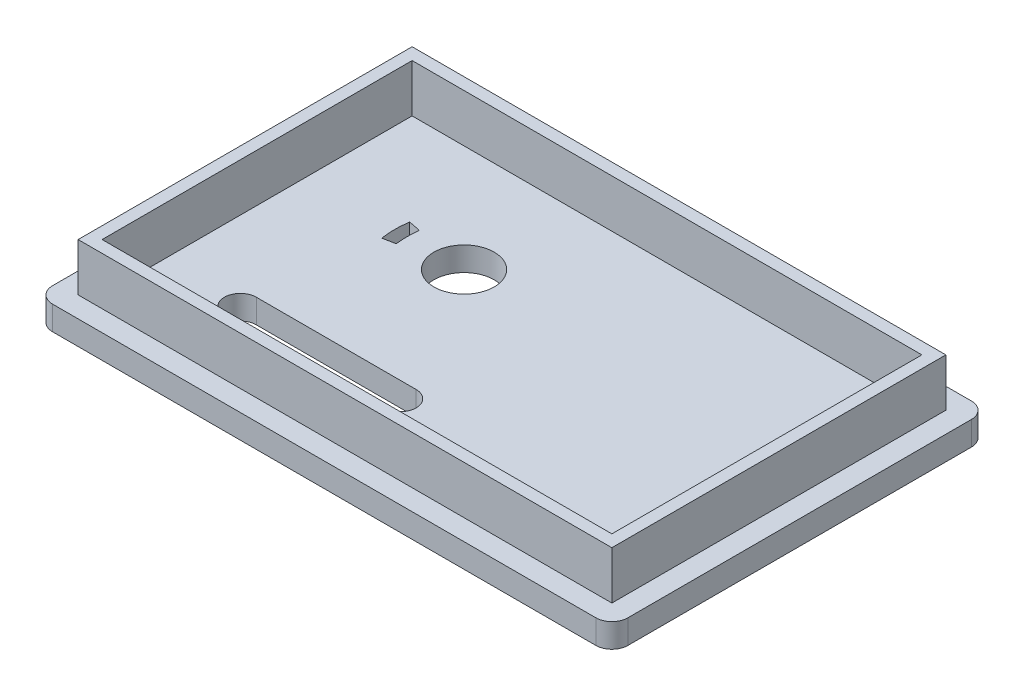
SolidWorks part; units mm, degrees
ref_plane "Front Plane" through (0, 0, 0) normal (0, 0, 1) x (1, 0, 0)
ref_plane "Top Plane" through (0, 0, 0) normal (0, 1, 0) x (1, 0, 0)
ref_plane "Right Plane" through (0, 0, 0) normal (1, 0, 0) x (0, 0, -1)
sketch "Sketch2" plane through (0, 0, 0) normal (0, 1, 0) x (1, 0, 0)
  line L1 (0, 0) -> (72, 0)
  line L2 (0, 0) -> (0, 47)
  line L3 (0, 47) -> (72, 47)
  line L4 (72, 0) -> (72, 47)
  dimension "D1" = 72
  dimension "D2" = 47
extrude "Boss-Extrude1" add sketch "Sketch2" along normal blind 3 contours L3 L4 L1 L2
fillet "Fillet1" radius 2 4 edges at (0, 1.5, 0) (0, 1.5, -47) (72, 1.5, -47) (72, 1.5, 0)
sketch "Sketch3" plane through (0, 3, 0) normal (0, 1, 0) x (1, 0, 0)
  line L0 (0, 2) -> (0, 45) construction
  line L1 (2.5, 44.5) -> (69.5, 44.5) construction
  line L2 (2.5, 44.5) -> (2.5, 2.5) construction
  line L3 (2.5, 2.5) -> (69.5, 2.5) construction
  line L4 (69.5, 44.5) -> (69.5, 2.5) construction
  line L5 (2, 0) -> (70, 0) construction
  line L6 (2.6, 44.4) -> (69.4, 44.4)
  line L7 (69.4, 44.4) -> (69.4, 2.6)
  line L8 (2.6, 2.6) -> (69.4, 2.6)
  line L9 (2.6, 44.4) -> (2.6, 2.6)
  line L10 (4.1, 42.9) -> (67.9, 42.9)
  line L11 (67.9, 42.9) -> (67.9, 4.1)
  line L12 (4.1, 4.1) -> (67.9, 4.1)
  line L13 (4.1, 42.9) -> (4.1, 4.1)
  dimension "D1" = 67
  dimension "D2" = 42
  dimension "D3" = 2.5
  dimension "D4" = 2.5
  dimension "D5" = 0.1
  dimension "D6" = 1.5
extrude "Boss-Extrude2" add sketch "Sketch3" along normal blind 6
sketch "Sketch4" plane through (0, 0, 0) normal (0, -1, 0) x (1, 0, 0)
  line L0 (14, -11.5) -> (34, -11.5) construction
  line L1 (14, -9.5) -> (34, -9.5)
  line L2 (14, -13.5) -> (34, -13.5)
  line L3 (2, 0) -> (70, 0) construction
  line L4 (0, -2) -> (0, -45) construction
  arc A0 (14, -9.5) -> (14, -13.5) centre (14, -11.5) ccw
  arc A1 (34, -13.5) -> (34, -9.5) centre (34, -11.5) ccw
  point P2 (24, -11.5)
  dimension "D1" = 11.5
  dimension "D2" = 24
  dimension "D3" = 20
  dimension "D4" = 4
extrude "Cut-Extrude1" cut sketch "Sketch4" against normal blind 6
sketch "Sketch5" plane through (0, 0, 0) normal (0, -1, 0) x (1, 0, 0)
  line L0 (14, -13.5) -> (34, -13.5) construction
  circle A0 centre (24, -29.5) radius 3.775
  circle A1 centre (24, -29.5) radius 9 construction
  point P3 (24, -13.5)
  point P4 (0, 0)
  point P7 (24, -29.5)
  dimension "D1" = 7.55
  dimension "D2" = 18
  dimension "D3" = 16
extrude "Cut-Extrude2" cut sketch "Sketch5" against normal blind 10
sketch "Sketch7" plane through (0, 0, 0) normal (0, -1, 0) x (1, 0, 0)
  line L0 (24, -29.5) -> (9.9, -29.5) construction
  line L1 (16.95, -28.05) -> (15.45, -27.75)
  line L2 (16.95, -30.95) -> (15.45, -31.25)
  circle A1 centre (24, -29.5) radius 3.775 construction
  spline S0 degree 2 poles (16.95, -28.05) (16.7952, -29.5153) (16.95, -30.95) knots 0 0 0 0.544466 0.544466 0.544466
  spline S1 degree 2 poles (15.45, -27.75) (15.1661, -29.5259) (15.45, -31.25) knots 0 0 0 0.895639 0.895639 0.895639
  dimension "D2" = 7.05
  dimension "D1" = 1.45
  dimension "D3" = 1.5
extrude "Cut-Extrude3" cut sketch "Sketch7" against normal blind 10
